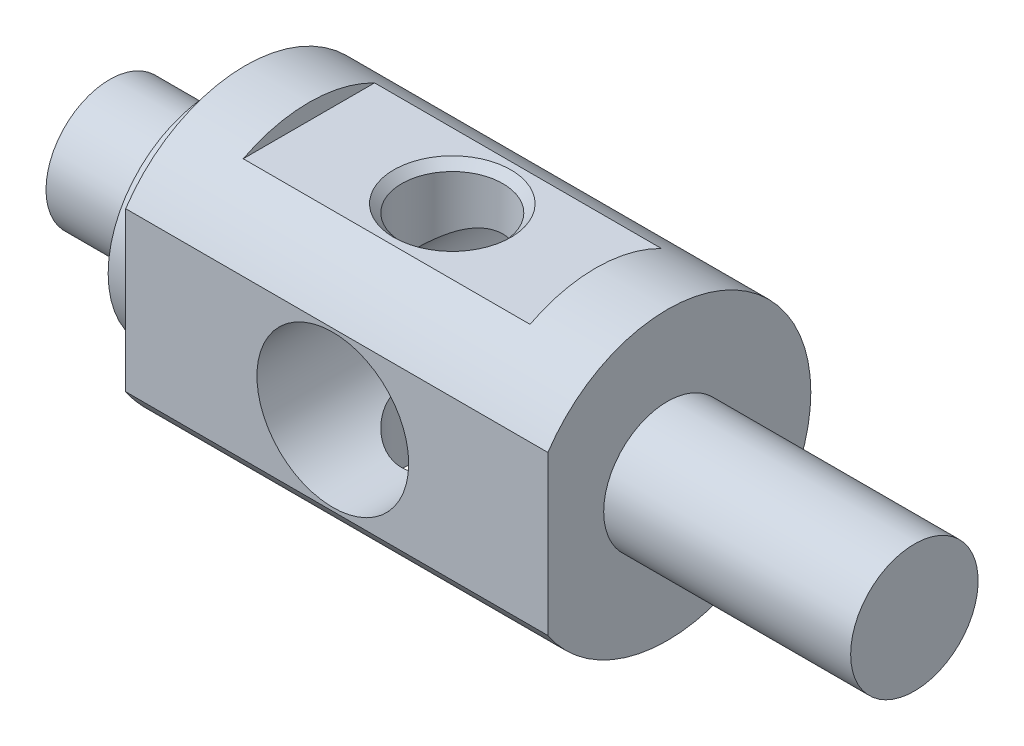
SolidWorks part; units mm, degrees
material "AISI 316 Annealed Stainless Steel Bar (SS)"
ref_plane "Front Plane" through (0, 0, 0) normal (0, 0, 1) x (1, 0, 0)
ref_plane "Top Plane" through (0, 0, 0) normal (0, 1, 0) x (1, 0, 0)
ref_plane "Right Plane" through (0, 0, 0) normal (1, 0, 0) x (0, 0, -1)
sketch "Sketch1" plane through (0, 0, 0) normal (0, 1, 0) x (1, 0, 0)
  line L0 (-21.5, 0) -> (29, 0)
  line L1 (29, 0) -> (29, 4)
  line L2 (29, 4) -> (13.5, 4)
  line L3 (13.5, 4) -> (13.5, 9)
  line L4 (13.5, 9) -> (-15, 9)
  line L5 (-15, 9) -> (-15, 4)
  line L6 (-15, 4) -> (-21.5, 4)
  line L7 (-21.5, 4) -> (-21.5, 0)
  line L8 (0, 0) -> (0, 9) construction
  dimension "D1" = 4
  dimension "D2" = 9
  dimension "D3" = 21.5
  dimension "D4" = 28.5
  dimension "D5" = 15
  dimension "D6" = 29
revolve "Revolve1" add sketch "Sketch1" angle 360 about L0
ref_plane "Plane1" through (0, 0, 9) normal (0, 0, 1) x (1, 0, 0)
sketch "Sketch2" plane through (0, 0, 9) normal (0, 0, 1) x (1, 0, 0)
  line L1 (-15, 6.35) -> (15, 6.35)
  line L2 (-15, 6.35) -> (-15, -6.35)
  line L3 (-15, -6.35) -> (15, -6.35)
  line L4 (15, 6.35) -> (15, -6.35)
  line L5 (-15, 9) -> (-15, -9) construction
  line L6 (-15, 0) -> (0, 0) construction
  line L7 (0, 0) -> (0, -6.35) construction
  dimension "D1" = 12.7
extrude "Cut-Extrude1" cut sketch "Sketch2" against normal blind 1.5 contours L4 L1 L2 L3
hole_wizard "M8x1.25 Tapped Hole1" [suppressed] positions "Sketch3" profile "Sketch4" tap size "M8x1.25" standard "ANSI Metric"
sketch "Sketch3" plane through (0, 0, 11.2) normal (0, 0, 1) x (1, 0, 0)
  point P0 (0, 0)
sketch "Sketch4" plane through (0, 0, 11.2) normal (1, 0, 0) x (0, -1, 0)
  line L0 (0, 0) -> (0, 23.9)
  line L1 (0, 23.9) -> (3.4, 23.9)
  line L2 (3.4, 23.9) -> (3.4, 0)
  line L5 (3.4, 0) -> (0, 0)
  line L11 (0, -6.35) -> (0, 107.95) construction
  dimension "Thru Tap Drill Dia." = 6.8
  dimension "Thru Tap Drill Depth" = 23.9
cosmetic thread "Hole Thread1" [suppressed] parameters "D2"=8
hole_wizard "#8-32 Tapped Hole1" positions "Sketch5" profile "Sketch6" tap size "#8-32" standard "ANSI Inch"
sketch "Sketch5" plane through (-21.5, 0, 0) normal (-1, 0, 0) x (0, 0, 1)
  point P0 (0, 0)
sketch "Sketch6" plane through (-21.5, 0, 0) normal (0, 1, 0) x (0, 0, 1)
  line L0 (0, 0) -> (0, 11.7478)
  line L1 (0, 11.7478) -> (1.7272, 10.71)
  line L2 (1.7272, 10.71) -> (1.7272, 0)
  line L5 (1.7272, 0) -> (0, 0)
  line L10 (0, 11.7478) -> (-1.7272, 10.71) construction
  line L11 (0, -6.35) -> (0, 107.95) construction
  dimension "Tap Drill Dia." = 3.4544
  dimension "Tap Drill Depth" = 10.71
  dimension "Drill Angle" = 118
cosmetic thread "Hole Thread2" parameters "D1"=8.33, "D2"=4.1656
sketch "Sketch7" plane through (-15, 0, 0) normal (-1, 0, 0) x (0, 0, 1)
  circle A0 centre (0, 0) radius 6.6
  dimension "D1" = 13.2
extrude "Cut-Extrude2" cut sketch "Sketch7" against normal blind 2 flip side to cut
sketch "Sketch8" plane through (13.5, 0, 0) normal (1, 0, 0) x (0, 0, -1)
  circle A1 centre (0, 0) radius 6.6
  circle A2 centre (0, 0) radius 6.6
  dimension "D1" = 0
extrude "Cut-Extrude3" [suppressed] cut sketch "Sketch8" against normal blind 1 flip side to cut
hole_wizard "3/8 (0.3750) Dowel Hole2" positions "Sketch9" profile "Sketch10" hole size "3/8" standard "ANSI Inch" end condition through all
sketch "Sketch9" plane through (0, 0, 7.5) normal (0, 0, 1) x (1, 0, 0)
  point P0 (0, 0)
sketch "Sketch10" plane through (0, 0, 7.5) normal (1, 0, 0) x (0, -1, 0)
  line L0 (0, 0) -> (0, 16.5)
  line L1 (0, 16.5) -> (4.7625, 16.5)
  line L2 (4.7625, 16.5) -> (4.7625, 0)
  line L5 (4.7625, 0) -> (0, 0)
  line L11 (0, -6.35) -> (0, 107.95) construction
  dimension "Thru Hole Dia." = 9.525
  dimension "Thru Hole Depth" = 16.5
sketch "Sketch11" plane through (0, 0, 0) normal (0, 1, 0) x (1, 0, 0)
  line L1 (9, -10) -> (-9, -10)
  line L2 (9, -10) -> (9, 10)
  line L3 (9, 10) -> (-9, 10)
  line L4 (-9, -10) -> (-9, 10)
  line L5 (9, -10) -> (-9, 10) construction
  line L6 (9, 10) -> (-9, -10) construction
  circle A0 centre (0, 0) radius 9 construction
  dimension "D1" = 18
  dimension "D2" = 18
  dimension "D3" = 20
extrude "Cut-Extrude4" cut sketch "Sketch11" against normal blind 1 from offset 9
hole_wizard "1/4 (0.2500) Dowel Hole1" positions "Sketch12" profile "Sketch13" hole size "1/4" standard "ANSI Inch" end condition through all
sketch "Sketch12" plane through (0, 8, 0) normal (0, 1, 0) x (1, 0, 0)
  point P0 (0, 0)
sketch "Sketch13" plane through (0, 8, 0) normal (1, 0, 0) x (0, 0, 1)
  line L0 (0, 0) -> (0, 17)
  line L1 (0, 17) -> (3.175, 17)
  line L2 (3.175, 17) -> (3.175, 0)
  line L5 (3.175, 0) -> (0, 0)
  line L11 (0, -6.35) -> (0, 107.95) construction
  dimension "Thru Hole Dia." = 6.35
  dimension "Thru Hole Depth" = 17
mirror "Mirror1" about plane through (0, 0, 0) normal (0, 1, 0) of "Cut-Extrude4"
chamfer "Chamfer1" distance 0.5 angle 45 1 edges at (0, 8, 3.175)
